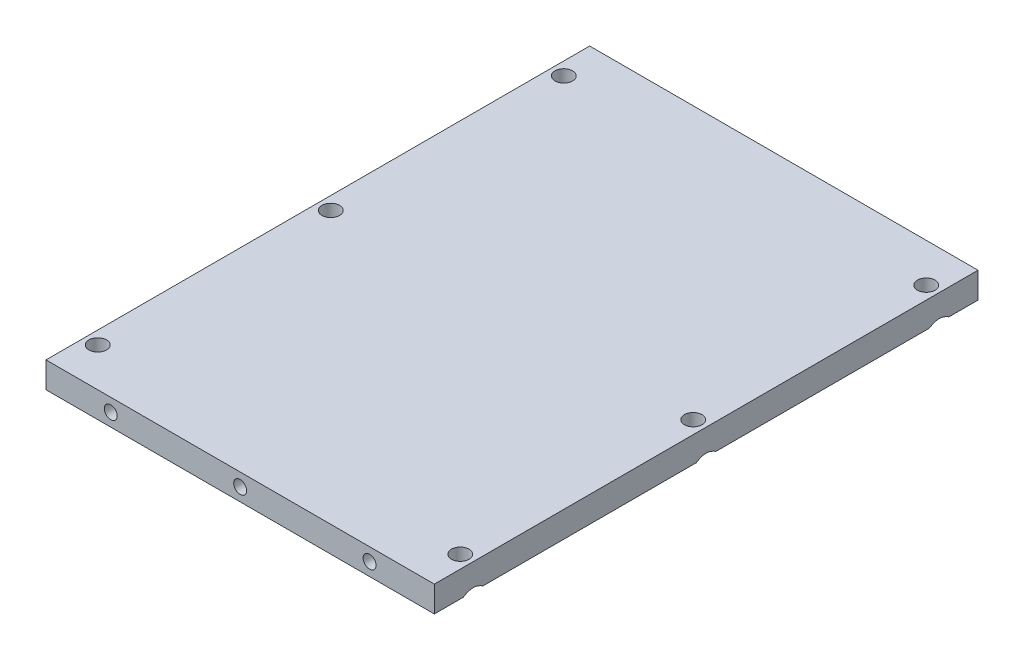
SolidWorks part; units mm, degrees
material "PA Тип 6"
ref_plane "Спереди" through (0, 0, 0) normal (0, 0, 1) x (1, 0, 0)
ref_plane "Сверху" through (0, 0, 0) normal (0, 1, 0) x (1, 0, 0)
ref_plane "Справа" through (0, 0, 0) normal (1, 0, 0) x (0, 0, -1)
sketch "Эскиз1" plane through (0, 0, 0) normal (0, 1, 0) x (1, 0, 0)
  line L1 (-37.5, 84) -> (37.5, 84)
  line L2 (-37.5, 84) -> (-37.5, -21)
  line L3 (-37.5, -21) -> (37.5, -21)
  line L4 (37.5, 84) -> (37.5, -21)
  point P7 (0, -21)
  dimension "D1" = 75
  dimension "D2" = 84
  dimension "D3" = 21
extrude "База" add sketch "Эскиз1" along normal blind 5
hole_wizard "КреплениеНиз-M3" positions "Эскиз46" profile "Эскиз47" tap size "M3" standard "ISO"
sketch "Эскиз46" plane through (0, 0, 21) normal (0, 0, 1) x (1, 0, 0)
  line L0 (0, 0) -> (0, 2.5) construction
  line L1 (0, 2.5) -> (0, 5) construction
  line L2 (37.5, 5) -> (-37.5, 5) construction
  line L11 (-25, 2.5) -> (0, 2.5) construction
  line L12 (0, 2.5) -> (25, 2.5) construction
  point P0 (-25, 2.5)
  point P3 (0, 2.5)
  point P6 (25, 2.5)
  dimension "D1" = 50
sketch "Эскиз47" plane through (-25, 2.5, 21) normal (1, 0, 0) x (0, -1, 0)
  line L0 (0, 0) -> (0, 10.7511)
  line L1 (0, 10.7511) -> (1.25, 10)
  line L2 (1.25, 10) -> (1.25, 0)
  line L5 (1.25, 0) -> (0, 0)
  line L10 (0, 10.7511) -> (-1.25, 10) construction
  line L11 (0, -6.35) -> (0, 107.95) construction
  dimension "Диаметр сверла" = 2.5
  dimension "Глубина сверла" = 10
  dimension "Угол заточки сверла" = 118
cosmetic thread "Отверстие резьбы3" parameters "D1"=8, "D2"=3
cosmetic thread "Отверстие резьбы4" parameters "D1"=8, "D2"=3
cosmetic thread "Отверстие резьбы5" parameters "D1"=8, "D2"=3
hole_wizard "КреплениеВерх-M3" positions "Эскиз51" profile "Эскиз53" tap size "M2" standard "DIN"
sketch "Эскиз51" plane through (0, 0, -84) normal (0, 0, -1) x (-1, 0, 0)
  line L0 (0, 0) -> (0, 2.5) construction
  line L1 (0, 2.5) -> (0, 5) construction
  line L2 (-37.5, 5) -> (37.5, 5) construction
  line L5 (-25, 2.5) -> (0, 2.5) construction
  line L6 (0, 2.5) -> (25, 2.5) construction
  point P0 (-25, 2.5)
  point P3 (0, 2.5)
  point P6 (25, 2.5)
  dimension "D1" = 50
sketch "Эскиз53" plane through (25, 2.5, -84) normal (1, 0, 0) x (0, 1, 0)
  line L0 (0, 0) -> (0, 10.4807)
  line L1 (0, 10.4807) -> (0.8, 10)
  line L2 (0.8, 10) -> (0.8, 0.225)
  line L3 (0.8, 0.225) -> (1.025, 0)
  line L5 (1.025, 0) -> (0, 0)
  line L6 (-0.8, 0.225) -> (-1.025, 0) construction
  line L10 (0, 10.4807) -> (-0.8, 10) construction
  line L11 (0, -6.35) -> (0, 107.95) construction
  dimension "Диаметр сверла" = 1.6
  dimension "Глубина сверла" = 10
  dimension "Диаметр передней зенковки" = 2.05
  dimension "Угол передней зенковки" = 90
  dimension "Угол заточки сверла" = 118
cosmetic thread "Отверстие резьбы10" parameters "D1"=8, "D2"=2
cosmetic thread "Отверстие резьбы11" parameters "D1"=8, "D2"=2
cosmetic thread "Отверстие резьбы12" parameters "D1"=8, "D2"=2
hole_wizard "Крепление-M3" positions "Эскиз54" profile "Эскиз55" countersink size "M3" standard "ISO" end condition through all
sketch "Эскиз54" plane through (0, 0, 0) normal (0, 1, 0) x (1, 0, 0)
  line L0 (-35, 76.5) -> (-35, 31.5) construction
  line L1 (-35, 31.5) -> (-35, -13.5) construction
  line L4 (35, -13.5) -> (35, 31.5) construction
  line L5 (35, 31.5) -> (35, 76.5) construction
  line L8 (-37.5, 84) -> (-37.5, -21) construction
  line L9 (37.5, -21) -> (37.5, 84) construction
  point P0 (-35, 31.5)
  point P2 (35, 31.5)
  point P4 (35, 76.5)
  point P6 (35, -13.5)
  point P8 (-35, -13.5)
  point P10 (-35, 76.5)
  point P26 (-37.5, 31.5)
  point P29 (37.5, 31.5)
  dimension "D1" = 90
  dimension "D2" = 2.5
  dimension "D3" = 2.5
sketch "Эскиз55" plane through (-35, 0, -31.5) normal (1, 0, 0) x (0, 0, -1)
  line L0 (0, 0) -> (0, 5)
  line L1 (0, 5) -> (1.7, 5)
  line L2 (1.7, 5) -> (1.7, 1.45)
  line L3 (1.7, 1.45) -> (3.15, 0)
  line L5 (3.15, 0) -> (0, 0)
  line L6 (-1.7, 1.45) -> (-3.15, 0) construction
  line L11 (0, -6.35) -> (0, 107.95) construction
  dimension "Диаметр сквозного отверстия" = 3.4
  dimension "Глубина сквозного отверстия" = 5
  dimension "Диаметр передней зенковки" = 6.3
  dimension "Угол передней зенковки" = 90
